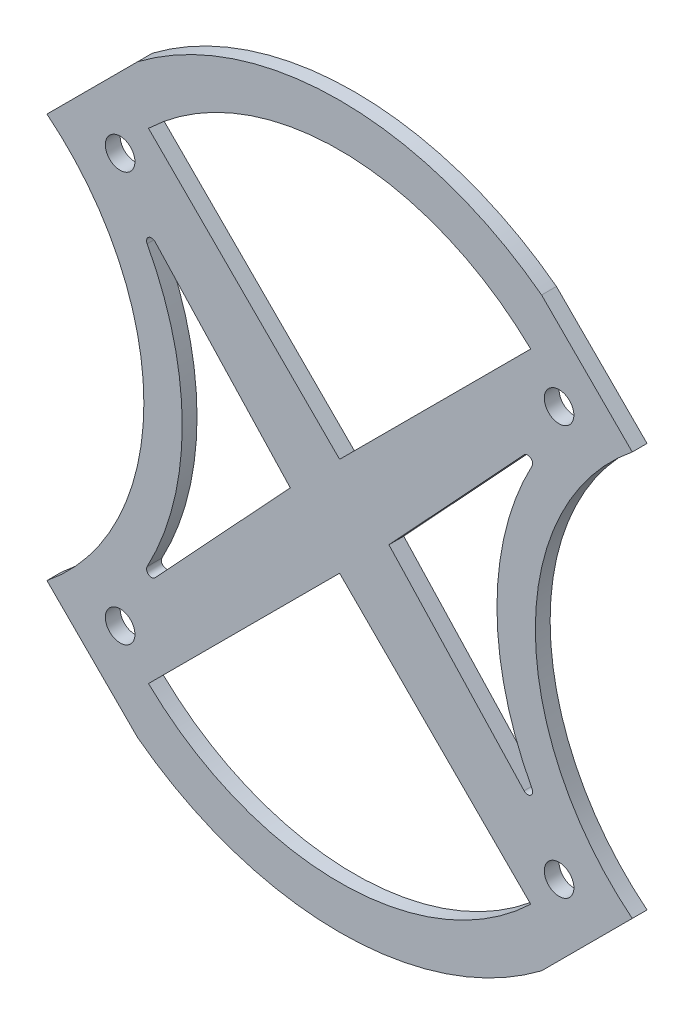
SolidWorks part; units mm, degrees
ref_plane "Front Plane" through (0, 0, 0) normal (0, 0, 1) x (1, 0, 0)
ref_plane "Top Plane" through (0, 0, 0) normal (0, 1, 0) x (1, 0, 0)
ref_plane "Right Plane" through (0, 0, 0) normal (1, 0, 0) x (0, 0, -1)
sketch "Sketch1" plane through (0, 0, 0) normal (0, 0, 1) x (1, 0, 0)
  line L1 (164.7, -164.7) -> (-164.7, -164.7) construction
  line L2 (164.7, -164.7) -> (164.7, 164.7) construction
  line L3 (164.7, 164.7) -> (-164.7, 164.7) construction
  line L4 (-164.7, -164.7) -> (-164.7, 164.7) construction
  line L5 (164.7, -164.7) -> (-164.7, 164.7) construction
  line L6 (164.7, 164.7) -> (-164.7, -164.7) construction
  line L11 (-164.7, 164.7) -> (-44.4918, 44.4918)
  line L12 (164.7, 164.7) -> (44.4918, 44.4918)
  line L16 (164.7, -164.7) -> (44.4918, -44.4918)
  line L17 (-164.7, -164.7) -> (-44.4918, -44.4918)
  circle A0 centre (-164.7, 164.7) radius 139.7 construction
  circle A1 centre (164.7, 164.7) radius 139.7 construction
  circle A2 centre (-164.7, -164.7) radius 139.7 construction
  circle A3 centre (164.7, -164.7) radius 139.7 construction
  circle A4 centre (-44.4918, 44.4918) radius 5
  circle A5 centre (44.4918, 44.4918) radius 5
  circle A6 centre (44.4918, -44.4918) radius 5
  circle A7 centre (-44.4918, -44.4918) radius 5
  point P0 (0, 0)
  point P10 (0, 0)
  dimension "D3" = 279.4
  dimension "D5" = 10
  dimension "D1" = 329.4
  dimension "D2" = 329.4
  dimension "D4" = 170
extrude "Boss-Extrude1" add sketch "Sketch1" along normal blind 0.1
sketch "Sketch2" plane through (0, 0, 0) normal (0, 0, 1) x (1, 0, 0)
  line L0 (-59.3411, 40.9563) -> (-40.9563, 59.3411)
  line L1 (-164.7, 164.7) -> (-44.4918, 44.4918) construction
  line L2 (164.7, 164.7) -> (-164.7, -164.7) construction
  line L3 (164.7, -164.7) -> (-164.7, 164.7) construction
  line L4 (164.7, 164.7) -> (-164.7, -164.7) construction
  line L5 (164.7, -164.7) -> (-164.7, 164.7) construction
  line L6 (40.9563, -59.3411) -> (59.3411, -40.9563)
  line L7 (1.65, 0) -> (-1.65, 0) construction
  line L8 (40.9563, 59.3411) -> (59.3411, 40.9563)
  line L9 (-59.3411, -40.9563) -> (-40.9563, -59.3411)
  line L10 (0, -1.65) -> (0, 1.65) construction
  line L15 (-38.7508, 48.7508) -> (0, 10)
  line L16 (0, 10) -> (38.7508, 48.7508)
  line L17 (-37.4101, 29.4957) -> (-10, 0)
  line L18 (10, 0) -> (37.4101, -29.4957)
  line L19 (37.4101, 29.4957) -> (10, 0)
  line L20 (0, -10) -> (38.7508, -48.7508)
  line L21 (-38.7508, -48.7508) -> (0, -10)
  line L22 (-10, 0) -> (-37.4101, -29.4957)
  arc A0 (-40.9563, 59.3411) -> (40.9563, 59.3411) centre (0, 5.0587) cw
  arc A1 (-59.3411, 40.9563) -> (-59.3411, -40.9563) centre (-92.1866, 0) cw
  arc A2 (-40.9563, -59.3411) -> (40.9563, -59.3411) centre (0, -5.0587) ccw
  arc A3 (59.3411, 40.9563) -> (59.3411, -40.9563) centre (92.1866, 0) ccw
  arc A4 (-38.7508, 48.7508) -> (38.7508, 48.7508) centre (0, 8.3234) cw
  arc A7 (-39.0241, 28.3426) -> (-39.0241, -28.3426) centre (-91.9079, 0) cw
  arc A8 (-37.4101, -29.4957) -> (-39.0241, -28.3426) centre (-38.1427, -28.815) cw
  arc A9 (-39.0241, 28.3426) -> (-37.4101, 29.4957) centre (-38.1427, 28.815) cw
  arc A10 (39.0241, 28.3426) -> (39.0241, -28.3426) centre (91.9079, 0) ccw
  arc A11 (37.4101, -29.4957) -> (39.0241, -28.3426) centre (38.1427, -28.815) ccw
  arc A12 (39.0241, 28.3426) -> (37.4101, 29.4957) centre (38.1427, 28.815) ccw
  arc A13 (-38.7508, -48.7508) -> (38.7508, -48.7508) centre (0, -8.3234) ccw
  point P4 (-50.1487, 50.1487)
  point P27 (45.0798, 41.0755)
  point P29 (45.0798, -41.0755)
  point P33 (-47.956, -40.8441)
  point P35 (-47.956, 40.8441)
  point P45 (-31.9079, 0)
  point P67 (0, 64.3234)
  dimension "D3" = 52.5
  dimension "D4" = 68
  dimension "D8" = 60
  dimension "D5" = 56
  dimension "D9" = 1
  dimension "D1" = 26
  dimension "D2" = 8
  dimension "D6" = 10
  dimension "D7" = 10
  dimension "D10" = 90
extrude "Boss-Extrude2" add sketch "Sketch2" along normal blind 3
sketch "Sketch3" plane through (0, 0, 3) normal (0, 0, 1) x (1, 0, 0)
  line L1 (44.5, -41.5) -> (-44.5, -41.5) construction
  line L2 (44.5, -41.5) -> (44.5, 41.5) construction
  line L3 (44.5, 41.5) -> (-44.5, 41.5) construction
  line L4 (-44.5, -41.5) -> (-44.5, 41.5) construction
  line L5 (44.5, -41.5) -> (-44.5, 41.5) construction
  line L6 (44.5, 41.5) -> (-44.5, -41.5) construction
  circle A0 centre (-44.5, -41.5) radius 3
  circle A1 centre (44.5, -41.5) radius 3
  circle A2 centre (44.5, 41.5) radius 3
  circle A3 centre (-44.5, 41.5) radius 3
  point P0 (0, 0)
  dimension "D4" = 6
  dimension "D1" = 89
  dimension "D2" = 89
  dimension "D3" = 83
extrude "Cut-Extrude1" cut sketch "Sketch3" against normal blind 3
